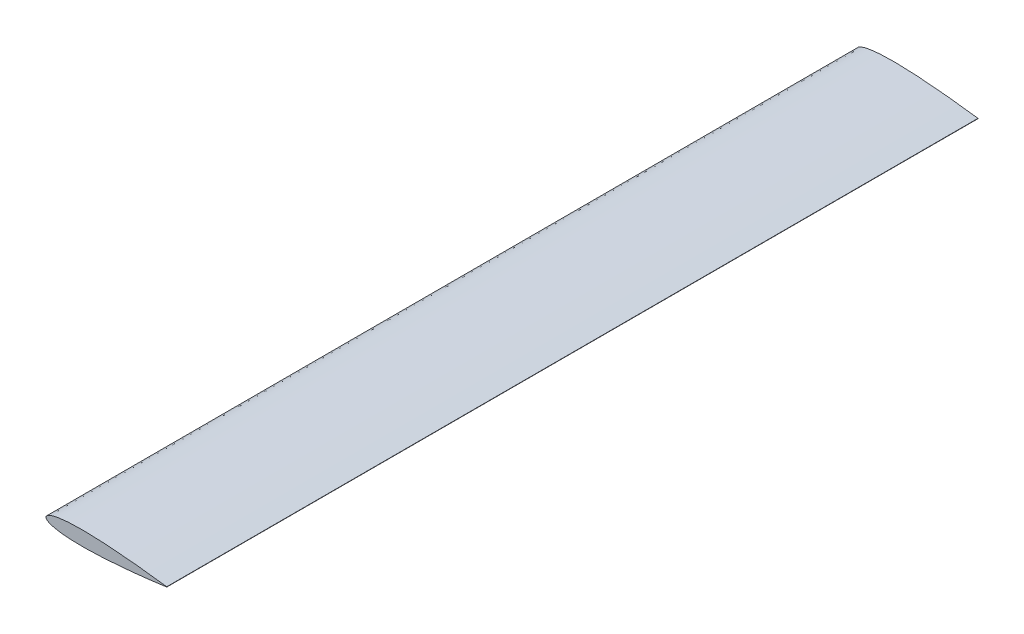
SolidWorks part; units mm, degrees
ref_plane "Front Plane" through (0, 0, 0) normal (0, 0, 1) x (1, 0, 0)
ref_plane "Top Plane" through (0, 0, 0) normal (0, 1, 0) x (1, 0, 0)
ref_plane "Right Plane" through (0, 0, 0) normal (1, 0, 0) x (0, 0, -1)
curve "Curve1"
  spline degree 3 poles (25, 0.0315, 0) (24.9951, 0.0322, 0) (24.9757, 0.0349, 0) (24.932, 0.041, 0) (24.8592, 0.0512, 0) (24.7576, 0.0653, 0) (24.6273, 0.0833, 0) (24.4688, 0.1051, 0) (24.2822, 0.1305, 0) (24.0682, 0.1594, 0) (23.8271, 0.1915, 0) (23.5596, 0.2267, 0) (23.2663, 0.2649, 0) (22.9478, 0.3057, 0) (22.6049, 0.349, 0) (22.2384, 0.3944, 0) (21.8492, 0.4419, 0) (21.4381, 0.4911, 0) (21.0061, 0.5418, 0) (20.5543, 0.5938, 0) (20.0837, 0.6467, 0) (19.5954, 0.7004, 0) (19.0904, 0.7546, 0) (18.5701, 0.809, 0) (18.0357, 0.8633, 0) (17.4883, 0.9174, 0) (16.9292, 0.9709, 0) (16.3598, 1.0235, 0) (15.7814, 1.075, 0) (15.1953, 1.1251, 0) (14.6029, 1.1733, 0) (14.0056, 1.2196, 0) (13.4048, 1.2634, 0) (12.8019, 1.3046, 0) (12.1983, 1.3427, 0) (11.5954, 1.3775, 0) (10.9946, 1.4086, 0) (10.3973, 1.4357, 0) (9.8049, 1.4585, 0) (9.2188, 1.4768, 0) (8.6403, 1.4901, 0) (8.0709, 1.4984, 0) (7.5118, 1.5014, 0) (6.9644, 1.4988, 0) (6.4299, 1.4905, 0) (5.9095, 1.4764, 0) (5.4046, 1.4565, 0) (4.9162, 1.4306, 0) (4.4455, 1.3988, 0) (3.9936, 1.3611, 0) (3.5615, 1.3177, 0) (3.1504, 1.2685, 0) (2.761, 1.2139, 0) (2.3944, 1.154, 0) (2.0513, 1.089, 0) (1.7326, 1.0192, 0) (1.439, 0.9449, 0) (1.1711, 0.8663, 0) (0.9296, 0.7837, 0) (0.7149, 0.6974, 0) (0.5275, 0.6077, 0) (0.3678, 0.5148, 0) (0.2359, 0.4187, 0) (0.132, 0.3194, 0) (0.0565, 0.2165, 0) (0.0103, 0.1097, 0) (-0.005, 0, 0) (0.0103, -0.1097, 0) (0.0565, -0.2165, 0) (0.132, -0.3194, 0) (0.2359, -0.4187, 0) (0.3678, -0.5148, 0) (0.5275, -0.6077, 0) (0.7149, -0.6974, 0) (0.9296, -0.7837, 0) (1.1711, -0.8663, 0) (1.439, -0.9449, 0) (1.7326, -1.0192, 0) (2.0513, -1.089, 0) (2.3944, -1.154, 0) (2.761, -1.2139, 0) (3.1504, -1.2685, 0) (3.5615, -1.3177, 0) (3.9936, -1.3611, 0) (4.4455, -1.3988, 0) (4.9162, -1.4306, 0) (5.4046, -1.4565, 0) (5.9095, -1.4764, 0) (6.4299, -1.4905, 0) (6.9644, -1.4988, 0) (7.5118, -1.5014, 0) (8.0709, -1.4984, 0) (8.6403, -1.4901, 0) (9.2188, -1.4768, 0) (9.8049, -1.4585, 0) (10.3973, -1.4357, 0) (10.9946, -1.4086, 0) (11.5954, -1.3775, 0) (12.1983, -1.3427, 0) (12.8019, -1.3046, 0) (13.4048, -1.2634, 0) (14.0056, -1.2196, 0) (14.6029, -1.1733, 0) (15.1953, -1.1251, 0) (15.7814, -1.075, 0) (16.3598, -1.0235, 0) (16.9292, -0.9709, 0) (17.4883, -0.9174, 0) (18.0357, -0.8633, 0) (18.5701, -0.809, 0) (19.0904, -0.7546, 0) (19.5954, -0.7004, 0) (20.0837, -0.6467, 0) (20.5543, -0.5938, 0) (21.0061, -0.5418, 0) (21.4381, -0.4911, 0) (21.8492, -0.4419, 0) (22.2384, -0.3944, 0) (22.6049, -0.349, 0) (22.9478, -0.3057, 0) (23.2663, -0.2649, 0) (23.5596, -0.2267, 0) (23.8271, -0.1915, 0) (24.0682, -0.1594, 0) (24.2822, -0.1305, 0) (24.4688, -0.1051, 0) (24.6273, -0.0833, 0) (24.7576, -0.0653, 0) (24.8592, -0.0512, 0) (24.932, -0.041, 0) (24.9757, -0.0349, 0) (24.9951, -0.0322, 0) (25, -0.0315, 0) knots 0 0 0 0 0.000289 0.001156 0.002598 0.004612 0.007194 0.010336 0.014031 0.018271 0.023046 0.028343 0.03415 0.040454 0.047239 0.054489 0.062186 0.070314 0.078852 0.08778 0.097077 0.106722 0.116691 0.126961 0.137507 0.148306 0.159331 0.170557 0.181957 0.193504 0.205172 0.216932 0.228758 0.240621 0.252495 0.26435 0.276161 0.287898 0.299536 0.311047 0.322405 0.333584 0.344559 0.355306 0.3658 0.376018 0.385938 0.395538 0.404798 0.413699 0.422222 0.430349 0.438066 0.445357 0.452209 0.458611 0.464554 0.47003 0.475035 0.479569 0.483637 0.48725 0.490432 0.493219 0.495674 0.497891 0.5 0.502109 0.504326 0.506781 0.509568 0.51275 0.516363 0.520431 0.524965 0.52997 0.535446 0.541389 0.547791 0.554643 0.561934 0.569651 0.577778 0.586301 0.595202 0.604462 0.614062 0.623982 0.6342 0.644694 0.655441 0.666416 0.677595 0.688953 0.700464 0.712102 0.723839 0.73565 0.747505 0.759379 0.771242 0.783068 0.794828 0.806496 0.818043 0.829443 0.840669 0.851694 0.862493 0.873039 0.883309 0.893278 0.902923 0.91222 0.921148 0.929686 0.937814 0.945511 0.952761 0.959546 0.96585 0.971657 0.976954 0.981729 0.985969 0.989664 0.992806 0.995388 0.997402 0.998844 0.999711 1 1 1 1
sketch "Sketch1" plane through (0, 0, 0) normal (0, 0, 1) x (1, 0, 0)
  line L0 (25, 0.0315) -> (25, -0.0315)
  spline S0 degree 3 poles (327.0229, 1976.9223) (41.0847, -3.4344) (33.104, -1.1028) (24.932, 0.041) (24.7629, 0.0647) (24.3944, 0.1155) (23.9608, 0.1739) (23.5596, 0.2267) (23.2663, 0.2649) (22.2644, 0.3932) (21.2027, 0.5208) (19.9154, 0.6656) (19.0753, 0.7569) (18.023, 0.8654) (16.9191, 0.9728) (15.9714, 1.0588) (14.9962, 1.1421) (14.0024, 1.2211) (13.0025, 1.2919) (11.998, 1.3553) (11.1958, 1.3994) (10.3973, 1.4357) (9.8049, 1.4585) (9.2188, 1.4768) (8.6403, 1.4901) (8.0709, 1.4984) (7.5118, 1.5014) (6.9644, 1.4988) (6.4299, 1.4905) (5.9095, 1.4764) (5.4046, 1.4565) (4.9162, 1.4306) (4.4455, 1.3988) (3.9936, 1.3611) (3.5615, 1.3177) (3.1504, 1.2685) (2.761, 1.2139) (2.3944, 1.154) (2.0513, 1.089) (1.7326, 1.0192) (1.439, 0.9449) (1.1711, 0.8663) (0.9296, 0.7837) (0.7149, 0.6974) (0.5275, 0.6077) (0.3678, 0.5148) (0.2359, 0.4187) (0.132, 0.3194) (0.0565, 0.2165) (0.0103, 0.1097) (-0.005, 0) (0.0103, -0.1097) (0.0565, -0.2165) (0.132, -0.3194) (0.2359, -0.4187) (0.3678, -0.5148) (0.5275, -0.6077) (0.7149, -0.6974) (0.9296, -0.7837) (1.1711, -0.8663) (1.439, -0.9449) (1.7326, -1.0192) (2.0513, -1.089) (2.3944, -1.154) (2.761, -1.2139) (3.1504, -1.2685) (3.5615, -1.3177) (3.9936, -1.3611) (4.4455, -1.3988) (4.9162, -1.4306) (5.4046, -1.4565) (5.9095, -1.4764) (6.4299, -1.4905) (6.9644, -1.4988) (7.5118, -1.5014) (8.0709, -1.4984) (8.6403, -1.4901) (9.2188, -1.4768) (9.8049, -1.4585) (10.3973, -1.4357) (11.1958, -1.3994) (11.998, -1.3553) (13.0025, -1.2919) (14.0024, -1.2211) (15.1893, -1.1267) (16.1644, -1.0416) (17.1119, -0.954) (18.1916, -0.849) (19.5518, -0.7068) (20.8237, -0.5639) (21.942, -0.4314) (22.6958, -0.338) (23.2663, -0.2649) (23.7115, -0.207) (24.1656, -0.1465) (24.599, -0.0873) (24.8158, -0.0573) (24.932, -0.041) (33.1039, 1.1028) (41.0847, 3.4344) (327.0211, -1976.9099) knots -0.482993 -0.482993 -0.482993 -0.482993 0.000289 0.001156 0.002598 0.010336 0.023046 0.028343 0.03415 0.040454 0.08778 0.097077 0.116691 0.137507 0.159331 0.181957 0.193504 0.216932 0.240621 0.252495 0.276161 0.287898 0.299536 0.311047 0.322405 0.333584 0.344559 0.355306 0.3658 0.376018 0.385938 0.395538 0.404798 0.413699 0.422222 0.430349 0.438066 0.445357 0.452209 0.458611 0.464554 0.47003 0.475035 0.479569 0.483637 0.48725 0.490432 0.493219 0.495674 0.497891 0.5 0.502109 0.504326 0.506781 0.509568 0.51275 0.516363 0.520431 0.524965 0.52997 0.535446 0.541389 0.547791 0.554643 0.561934 0.569651 0.577778 0.586301 0.595202 0.604462 0.614062 0.623982 0.6342 0.644694 0.655441 0.666416 0.677595 0.688953 0.700464 0.712102 0.723839 0.747505 0.759379 0.783068 0.806496 0.829443 0.840669 0.862493 0.893278 0.921148 0.937814 0.959546 0.96585 0.971657 0.985969 0.992806 0.997402 0.998844 0.999711 1.482992 1.482992 1.482992 1.482992 only from (25, 0.0315) to (25, -0.0315) construction
  spline S1 degree 3 poles (25, 0.0315) (24.9951, 0.0322) (24.9757, 0.0349) (24.932, 0.041) (24.7629, 0.0647) (24.3944, 0.1155) (23.9608, 0.1739) (23.5596, 0.2267) (23.2663, 0.2649) (22.2644, 0.3932) (21.2027, 0.5208) (19.9154, 0.6656) (19.0753, 0.7569) (18.023, 0.8654) (16.9191, 0.9728) (15.9714, 1.0588) (14.9962, 1.1421) (14.0024, 1.2211) (13.0025, 1.2919) (11.998, 1.3553) (11.1958, 1.3994) (10.3973, 1.4357) (9.8049, 1.4585) (9.2188, 1.4768) (8.6403, 1.4901) (8.0709, 1.4984) (7.5118, 1.5014) (6.9644, 1.4988) (6.4299, 1.4905) (5.9095, 1.4764) (5.4046, 1.4565) (4.9162, 1.4306) (4.4455, 1.3988) (3.9936, 1.3611) (3.5615, 1.3177) (3.1504, 1.2685) (2.761, 1.2139) (2.3944, 1.154) (2.0513, 1.089) (1.7326, 1.0192) (1.439, 0.9449) (1.1711, 0.8663) (0.9296, 0.7837) (0.7149, 0.6974) (0.5275, 0.6077) (0.3678, 0.5148) (0.2359, 0.4187) (0.132, 0.3194) (0.0565, 0.2165) (0.0103, 0.1097) (-0.005, 0) (0.0103, -0.1097) (0.0565, -0.2165) (0.132, -0.3194) (0.2359, -0.4187) (0.3678, -0.5148) (0.5275, -0.6077) (0.7149, -0.6974) (0.9296, -0.7837) (1.1711, -0.8663) (1.439, -0.9449) (1.7326, -1.0192) (2.0513, -1.089) (2.3944, -1.154) (2.761, -1.2139) (3.1504, -1.2685) (3.5615, -1.3177) (3.9936, -1.3611) (4.4455, -1.3988) (4.9162, -1.4306) (5.4046, -1.4565) (5.9095, -1.4764) (6.4299, -1.4905) (6.9644, -1.4988) (7.5118, -1.5014) (8.0709, -1.4984) (8.6403, -1.4901) (9.2188, -1.4768) (9.8049, -1.4585) (10.3973, -1.4357) (11.1958, -1.3994) (11.998, -1.3553) (13.0025, -1.2919) (14.0024, -1.2211) (15.1893, -1.1267) (16.1644, -1.0416) (17.1119, -0.954) (18.1916, -0.849) (19.5518, -0.7068) (20.8237, -0.5639) (21.942, -0.4314) (22.6958, -0.338) (23.2663, -0.2649) (23.7115, -0.207) (24.1656, -0.1465) (24.599, -0.0873) (24.8158, -0.0573) (24.932, -0.041) (24.9757, -0.0349) (24.9951, -0.0322) (25, -0.0315) knots 0 0 0 0 0.000289 0.001156 0.002598 0.010336 0.023046 0.028343 0.03415 0.040454 0.08778 0.097077 0.116691 0.137507 0.159331 0.181957 0.193504 0.216932 0.240621 0.252495 0.276161 0.287898 0.299536 0.311047 0.322405 0.333584 0.344559 0.355306 0.3658 0.376018 0.385938 0.395538 0.404798 0.413699 0.422222 0.430349 0.438066 0.445357 0.452209 0.458611 0.464554 0.47003 0.475035 0.479569 0.483637 0.48725 0.490432 0.493219 0.495674 0.497891 0.5 0.502109 0.504326 0.506781 0.509568 0.51275 0.516363 0.520431 0.524965 0.52997 0.535446 0.541389 0.547791 0.554643 0.561934 0.569651 0.577778 0.586301 0.595202 0.604462 0.614062 0.623982 0.6342 0.644694 0.655441 0.666416 0.677595 0.688953 0.700464 0.712102 0.723839 0.747505 0.759379 0.783068 0.806496 0.829443 0.840669 0.862493 0.893278 0.921148 0.937814 0.959546 0.96585 0.971657 0.985969 0.992806 0.997402 0.998844 0.999711 1 1 1 1
extrude "Boss-Extrude1" add sketch "Sketch1" along normal blind 168 contours S1 L0
